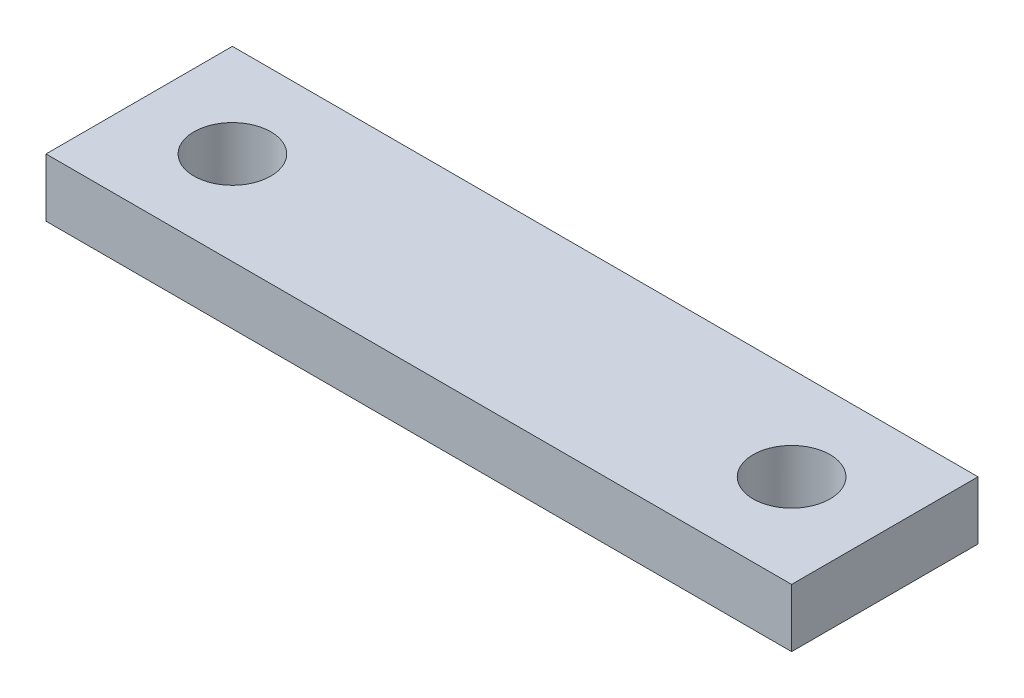
SolidWorks part; units mm, degrees
ref_plane "Front Plane" through (0, 0, 0) normal (0, 0, 1) x (1, 0, 0)
ref_plane "Top Plane" through (0, 0, 0) normal (0, 1, 0) x (1, 0, 0)
ref_plane "Right Plane" through (0, 0, 0) normal (1, 0, 0) x (0, 0, -1)
sketch "Sketch1" plane through (0, 0, 0) normal (0, 1, 0) x (1, 0, 0)
  line L1 (0, 0) -> (32, 0)
  line L2 (0, 0) -> (0, 8)
  line L3 (0, 8) -> (32, 8)
  line L4 (32, 0) -> (32, 8)
  dimension "D1" = 32
  dimension "D2" = 8
extrude "Boss-Extrude1" add sketch "Sketch1" along normal blind 2.5
sketch "Sketch2" plane through (0, 0, 0) normal (0, 1, 0) x (1, 0, 0)
  line L0 (0, 8) -> (0, 0) construction
  line L1 (0, 0) -> (32, 0) construction
  circle A0 centre (4, 4) radius 1.65
  circle A1 centre (28, 4) radius 1.65
  dimension "D1" = 3.3
  dimension "D2" = 4
  dimension "D3" = 4
  dimension "D4" = 2
extrude "Cut-Extrude1" cut sketch "Sketch2" along normal up to surface (2.5 mm away) up to face at (16, 2.5, -4)
